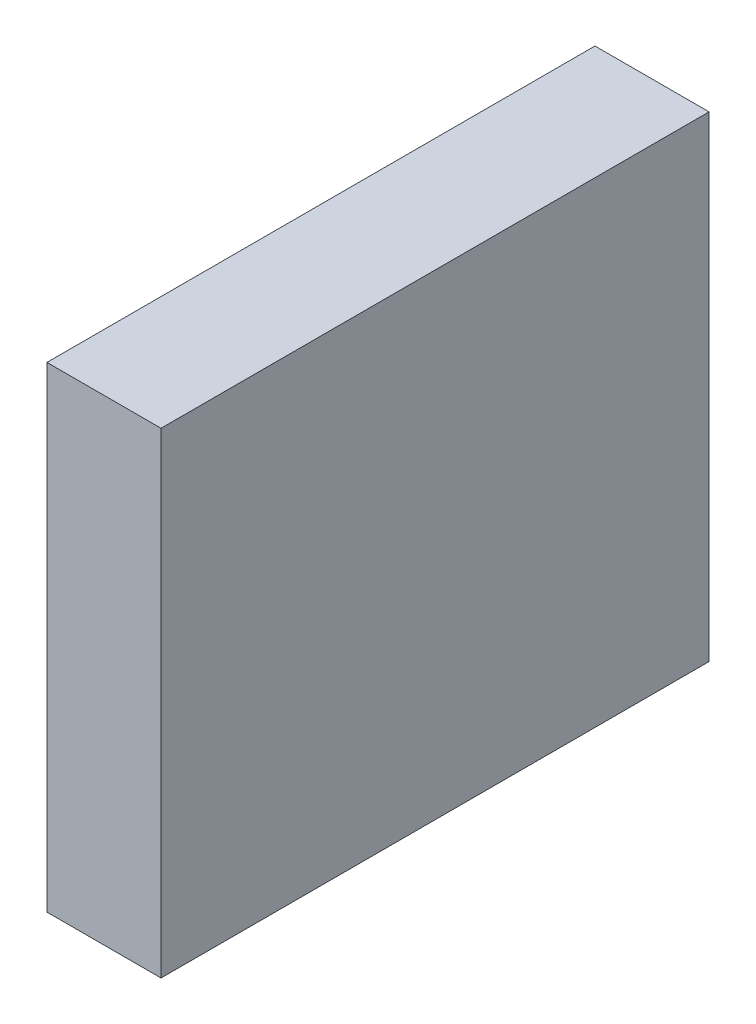
SolidWorks part; units mm, degrees
ref_plane "Front Plane" through (0, 0, 0) normal (0, 0, 1) x (1, 0, 0)
ref_plane "Top Plane" through (0, 0, 0) normal (0, 1, 0) x (1, 0, 0)
ref_plane "Right Plane" through (0, 0, 0) normal (1, 0, 0) x (0, 0, -1)
sketch "Sketch1" plane through (0, 0, 0) normal (0, 1, 0) x (1, 0, 0)
  line L1 (0, 0) -> (23, 0)
  line L2 (0, 0) -> (0, 110.5)
  line L3 (0, 110.5) -> (23, 110.5)
  line L4 (23, 0) -> (23, 110.5)
  dimension "D1" = 23
  dimension "D2" = 110.5
extrude "Boss-Extrude1" add sketch "Sketch1" along normal blind 96
